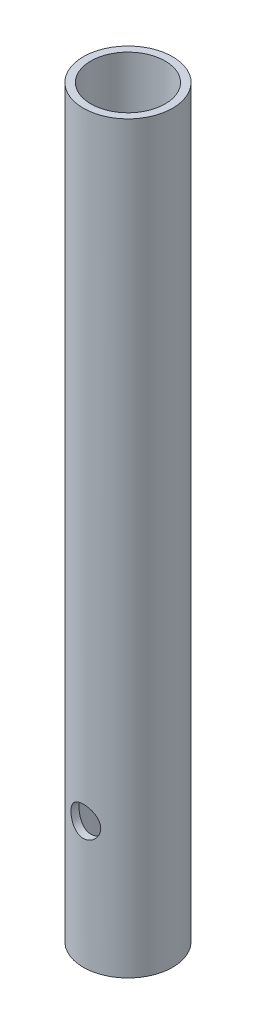
SolidWorks part; units mm, degrees
material "Thornel Mat VMA"
ref_plane "前视基准面" through (0, 0, 0) normal (0, 0, 1) x (1, 0, 0)
ref_plane "上视基准面" through (0, 0, 0) normal (0, 1, 0) x (1, 0, 0)
ref_plane "右视基准面" through (0, 0, 0) normal (1, 0, 0) x (0, 0, -1)
sketch "草图1" plane through (0, 0, 0) normal (0, 1, 0) x (1, 0, 0)
  circle A1 centre (0, 0) radius 6
  dimension "D1" = 12
extrude "拉伸-薄壁1" add sketch "草图1" along normal blind 100 thin thin type one direction reverse wall 1
sketch "草图2" plane through (0, 0, 0) normal (0, 0, 1) x (1, 0, 0)
  line L0 (-6, 0) -> (6, 0) construction
  circle A0 centre (0, 17) radius 2
  dimension "D1" = 4
  dimension "D2" = 17
extrude "切除-拉伸1" cut sketch "草图2" against normal through all both and the other way through all
